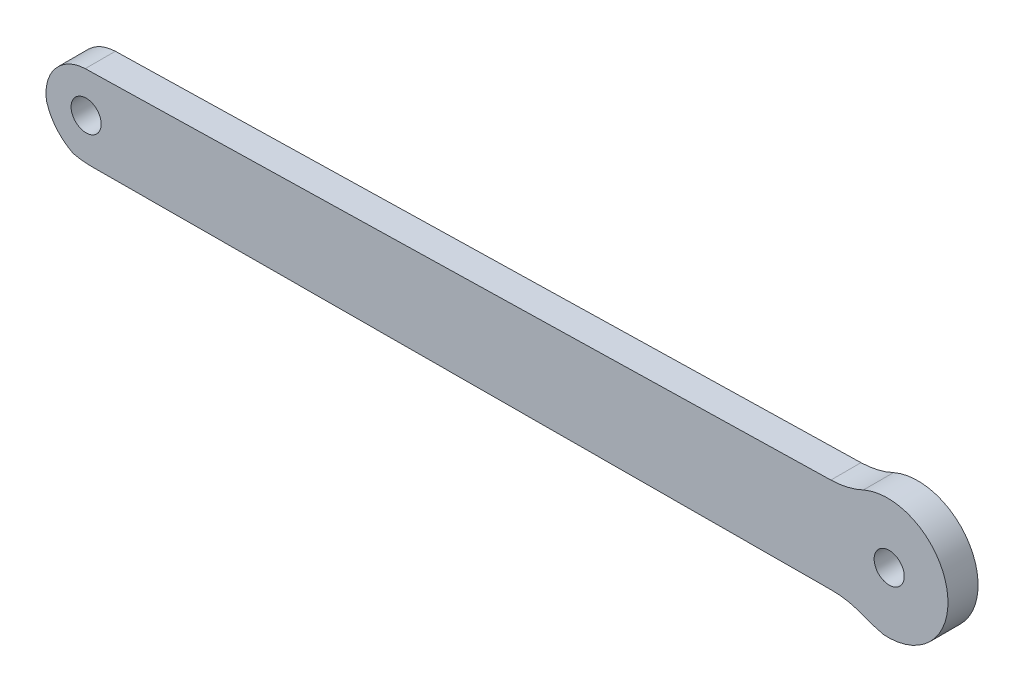
SolidWorks part; units mm, degrees
ref_plane "前基準面" through (0, 0, 0) normal (0, 0, 1) x (1, 0, 0)
ref_plane "上基準面" through (0, 0, 0) normal (0, 1, 0) x (1, 0, 0)
ref_plane "右基準面" through (0, 0, 0) normal (1, 0, 0) x (0, 0, -1)
sketch "草圖1" plane through (0, 0, 0) normal (0, 0, 1) x (1, 0, 0)
  line L0 (28.4308, 146.7728) -> (84.081, 147.0123) construction
  line L1 (83.9643, 156.4706) -> (9.6893, 154.824) construction
  line L2 (10.3363, 146.6949) -> (28.4308, 146.7728) construction
  line L3 (28.4308, 146.7728) -> (84.081, 147.0123)
  line L4 (83.9643, 156.4706) -> (9.6893, 154.824)
  line L5 (10.3363, 146.6949) -> (28.4308, 146.7728)
  circle A0 centre (89.7718, 151.8125) radius 1.5 construction
  arc A1 (83.9643, 156.4706) -> (87.2069, 157.2366) centre (83.7867, 164.469) ccw construction
  arc A2 (87.3415, 146.3267) -> (84.081, 147.0123) centre (84.1015, 139.014) ccw construction
  circle A3 centre (9.778, 150.825) radius 1.5 construction
  arc A4 (8.4935, 146.9019) -> (10.3363, 146.6949) centre (10.3021, 154.6954) ccw construction
  arc A5 (5.8251, 150.1299) -> (8.4935, 146.9019) centre (10.809, 151.5328) ccw construction
  arc A6 (9.6893, 154.824) -> (5.8251, 150.1299) centre (9.8585, 150.7471) ccw construction
  circle A7 centre (89.7718, 151.8125) radius 1.5
  arc A8 (83.9643, 156.4706) -> (87.2069, 157.2366) centre (83.7867, 164.469) ccw
  arc A9 (87.3415, 146.3267) -> (84.081, 147.0123) centre (84.1015, 139.014) ccw
  circle A10 centre (9.778, 150.825) radius 1.5
  arc A11 (8.4935, 146.9019) -> (10.3363, 146.6949) centre (10.3021, 154.6954) ccw
  arc A12 (5.8251, 150.1299) -> (8.4935, 146.9019) centre (10.809, 151.5328) ccw
  arc A13 (9.6893, 154.824) -> (5.8251, 150.1299) centre (9.8585, 150.7471) ccw
  arc A14 (89.2137, 145.7597) -> (87.2069, 157.2366) centre (89.6265, 151.7458) ccw
  arc A15 (95.2317, 149.6044) -> (87.2069, 157.2366) centre (89.6265, 151.7458) ccw construction
  arc A16 (87.3415, 146.3267) -> (89.2137, 145.7597) centre (93.7093, 163.9803) ccw
  point P0 (10.3363, 146.6949)
extrude "填料-伸長1" add sketch "草圖1" along normal blind 3
